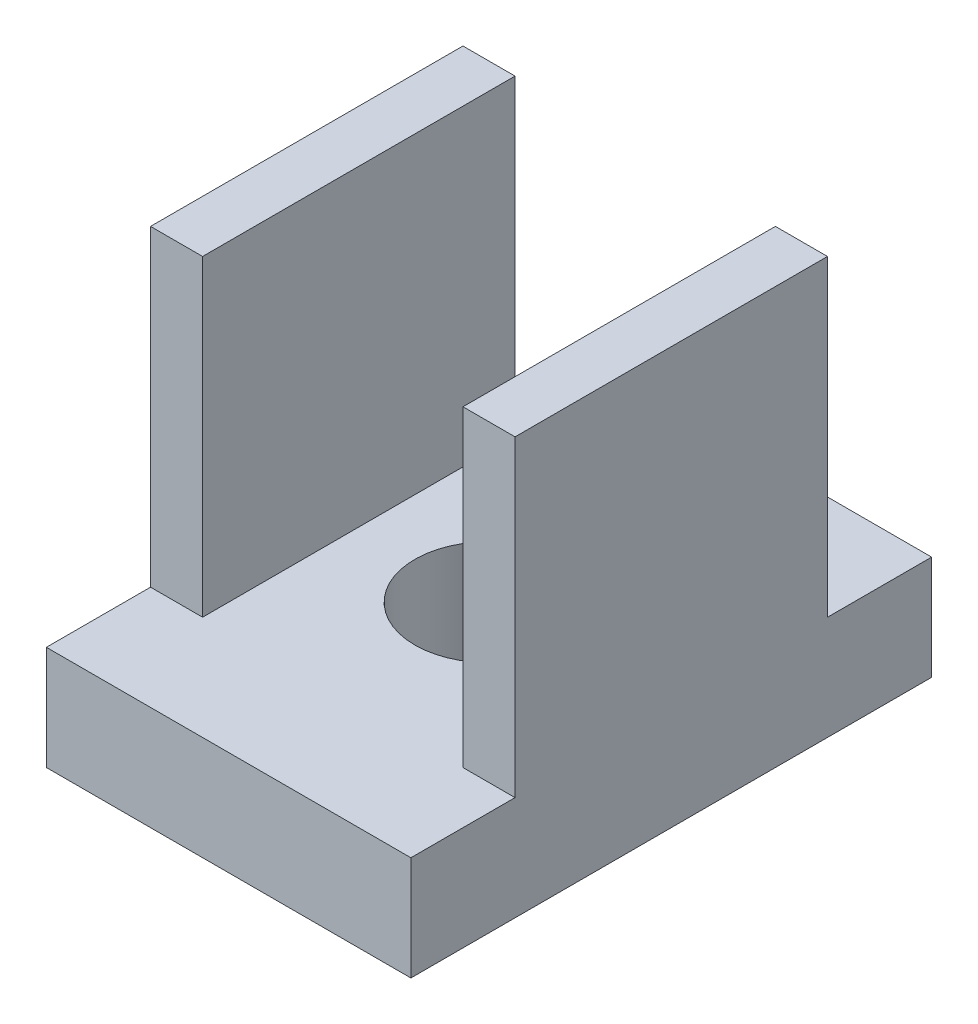
SolidWorks part; units mm, degrees
ref_plane "Front Plane" through (0, 0, 0) normal (0, 0, 1) x (1, 0, 0)
ref_plane "Top Plane" through (0, 0, 0) normal (0, 1, 0) x (1, 0, 0)
ref_plane "Right Plane" through (0, 0, 0) normal (1, 0, 0) x (0, 0, -1)
sketch "Sketch1" plane through (0, 0, 0) normal (0, 1, 0) x (1, 0, 0)
  line L1 (-3.5, 5) -> (3.5, 5)
  line L2 (-3.5, 5) -> (-3.5, -5)
  line L3 (-3.5, -5) -> (3.5, -5)
  line L4 (3.5, 5) -> (3.5, -5)
  line L5 (-3.5, 5) -> (3.5, -5) construction
  line L6 (-3.5, -5) -> (3.5, 5) construction
  point P0 (0, 0)
  dimension "D1" = 10
  dimension "D2" = 7
extrude "Boss-Extrude1" add sketch "Sketch1" along normal blind 2
sketch "Sketch2" plane through (0, 2, 0) normal (0, 1, 0) x (1, 0, 0)
  circle A0 centre (0, 0) radius 1.425
  dimension "D1" = 2.85
extrude "Cut-Extrude1" cut sketch "Sketch2" against normal through all
sketch "Sketch3" plane through (0, 2, 0) normal (0, 1, 0) x (1, 0, 0)
  line L0 (-3.5, 5) -> (-3.5, -5) construction
  line L1 (-3.5, -3) -> (-2.5, -3)
  line L2 (-3.5, -3) -> (-3.5, 3)
  line L3 (-3.5, 3) -> (-2.5, 3)
  line L4 (-2.5, -3) -> (-2.5, 3)
  line L5 (3.5, -5) -> (3.5, 5) construction
  line L6 (3.5, 3) -> (2.5, 3)
  line L7 (3.5, 3) -> (3.5, -3)
  line L8 (3.5, -3) -> (2.5, -3)
  line L9 (2.5, 3) -> (2.5, -3)
  line L10 (0, 0) -> (0, 5) construction
  line L11 (3.5, 5) -> (-3.5, 5) construction
  point P12 (-2.5, 0)
  dimension "D1" = 1
  dimension "D2" = 6
extrude "Boss-Extrude2" add sketch "Sketch3" along normal blind 6
